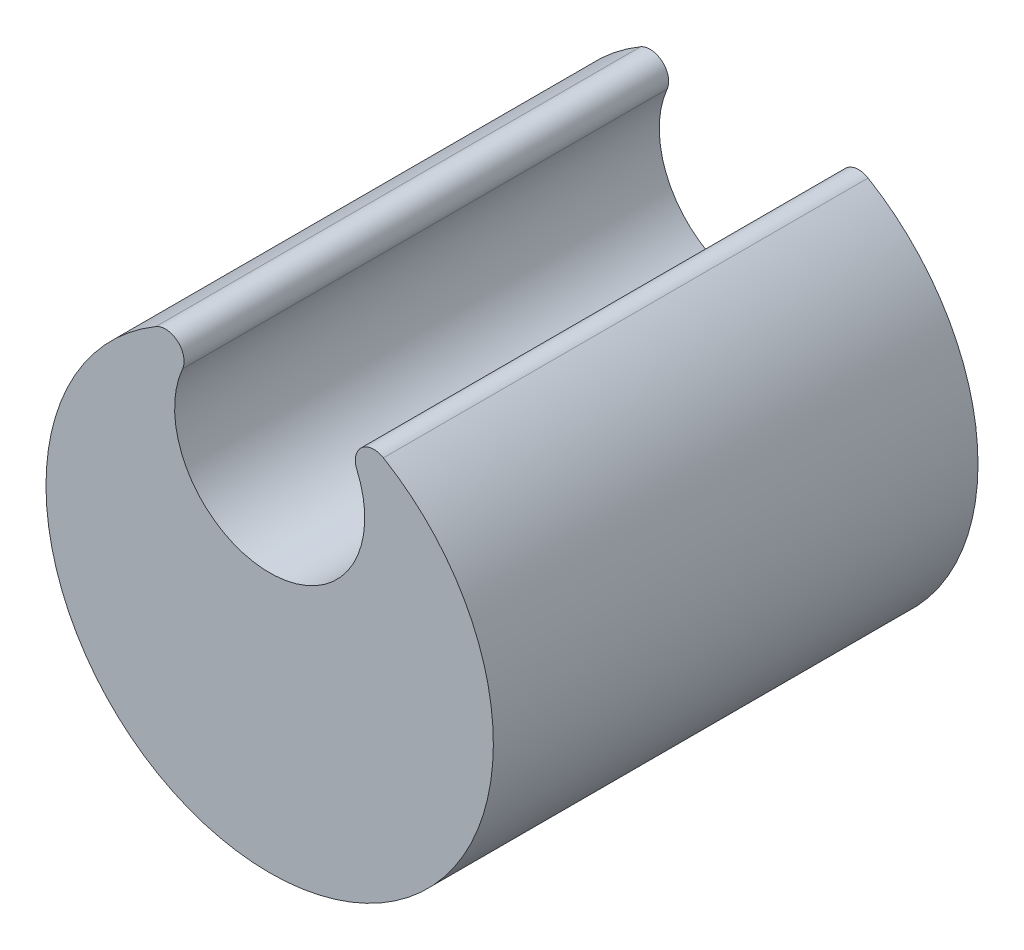
SolidWorks part; units mm, degrees
ref_plane "Front" through (0, 0, 0) normal (0, 0, 1) x (1, 0, 0)
ref_plane "Top" through (0, 0, 0) normal (0, 1, 0) x (1, 0, 0)
ref_plane "Right" through (0, 0, 0) normal (1, 0, 0) x (0, 0, -1)
sketch "Skizze1" plane through (0, 0, 0) normal (0, 0, 1) x (1, 0, 0)
  line L0 (0, 0) -> (0, 7.2203) construction
  circle A0 centre (0, 0) radius 6
  circle A1 centre (0, 3.5198) radius 2.55
  dimension "D1" = 12
  dimension "D2" = 5.1
extrude "Aufsatz-Linear austragen2" add sketch "Skizze1" along normal blind 13
fillet "Verrundung1" radius 0.5 2 edges at (-0.7718, 5.9502, 6.5) (0.7718, 5.9502, 6.5)
